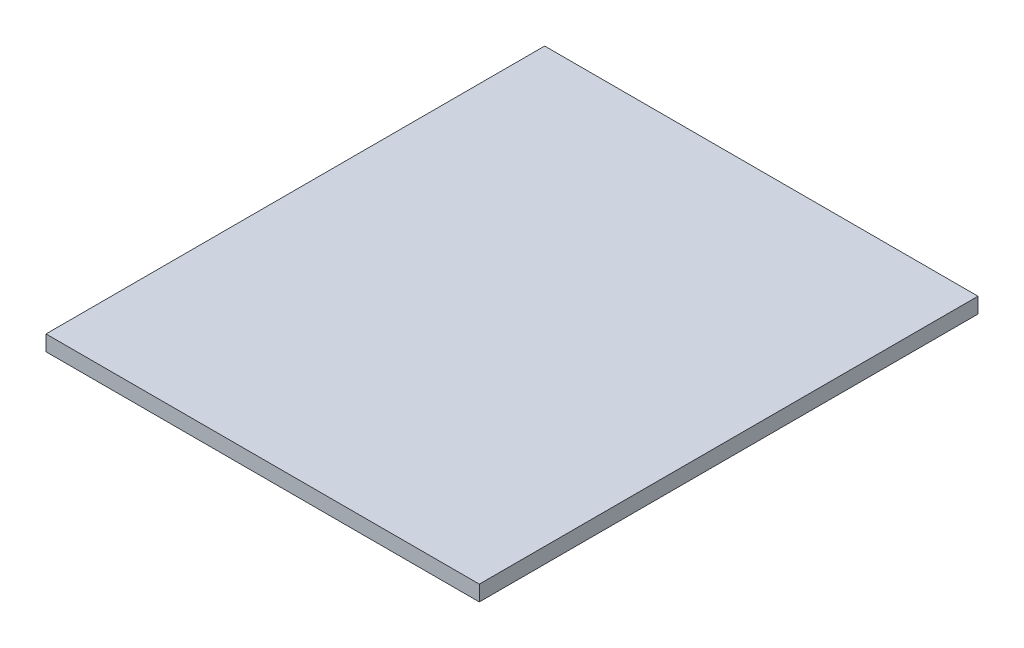
SolidWorks part; units mm, degrees
ref_plane "Front Plane" through (0, 0, 0) normal (0, 0, 1) x (1, 0, 0)
ref_plane "Top Plane" through (0, 0, 0) normal (0, 1, 0) x (1, 0, 0)
ref_plane "Right Plane" through (0, 0, 0) normal (1, 0, 0) x (0, 0, -1)
sketch "Sketch1" plane through (0, 0, 0) normal (0, 1, 0) x (1, 0, 0)
  line L1 (-63, -72.5) -> (63, -72.5)
  line L2 (-63, -72.5) -> (-63, 72.5)
  line L3 (-63, 72.5) -> (63, 72.5)
  line L4 (63, -72.5) -> (63, 72.5)
  line L5 (-63, -72.5) -> (63, 72.5) construction
  line L6 (-63, 72.5) -> (63, -72.5) construction
  point P0 (0, 0)
  dimension "D1" = 145
  dimension "D2" = 126
extrude "Boss-Extrude1" add sketch "Sketch1" along normal blind 4.5
